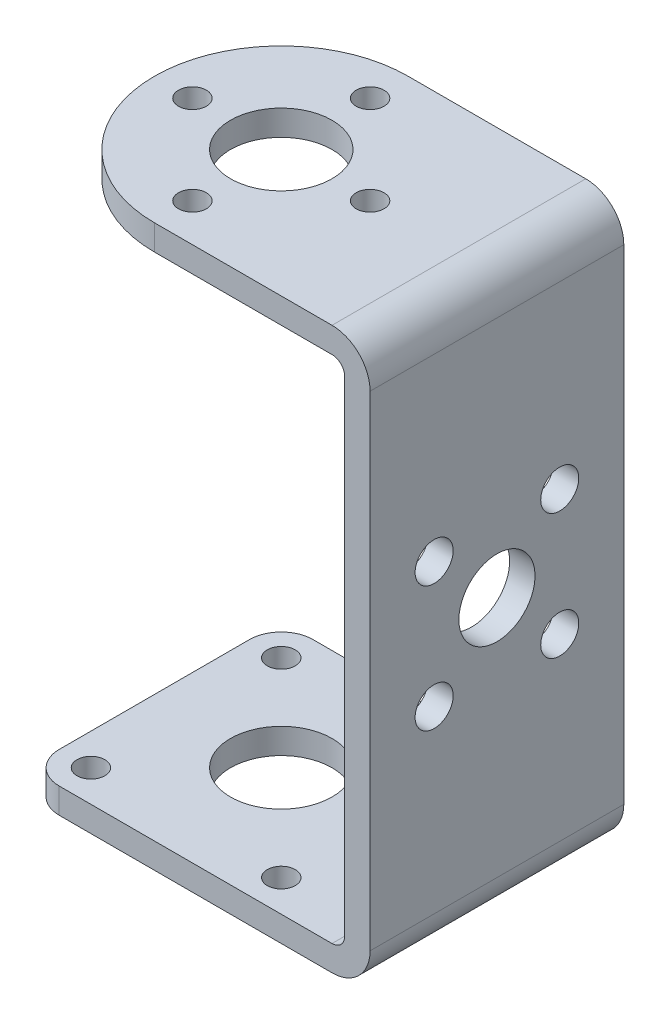
SolidWorks part; units mm, degrees
ref_plane "Front Plane" through (0, 0, 0) normal (0, 0, 1) x (1, 0, 0)
ref_plane "Top Plane" through (0, 0, 0) normal (0, 1, 0) x (1, 0, 0)
ref_plane "Right Plane" through (0, 0, 0) normal (1, 0, 0) x (0, 0, -1)
ref_plane "Plane4" through (0, -22.1, 0) normal (0, -1, 0) x (1, 0, 0)
sketch "Sketch1" plane through (0, -22.1, 0) normal (0, -1, 0) x (1, 0, 0)
  line L0 (17, 10) -> (0, 10)
  line L1 (0, -10) -> (17, -10)
  line L2 (17, -10) -> (17, 10)
  arc A0 (0, 10) -> (0, -10) centre (0, 0) ccw
extrude "Boss-Extrude1" add sketch "Sketch1" against normal blind 44.2
sketch "Sketch2" plane through (0, 0, -10) normal (0, 0, -1) x (-1, 0, 0)
  line L0 (0, -22.1) -> (0, 20.1)
  line L1 (0, 20.1) -> (-15, 20.1)
  line L2 (-15, 20.1) -> (-15, -22.1)
  line L3 (-15, -22.1) -> (0, -22.1)
extrude "Cut-Extrude1" cut sketch "Sketch2" against normal through all
sketch "Sketch3" plane through (15, 0, 0) normal (-1, 0, 0) x (0, 0, 1)
  line L0 (10, -22.1) -> (-10, -22.1)
  line L1 (-10, -22.1) -> (-10, -20.1)
  line L2 (-10, -20.1) -> (10, -20.1)
  line L3 (10, -20.1) -> (10, -22.1)
extrude "Boss-Extrude2" add sketch "Sketch3" along normal blind 25
hole_wizard "Ø3.0 (3) Diameter Hole1" positions "Sketch5" profile "Sketch4" hole size "Ø3.0" standard "ANSI Metric"
sketch "Sketch5" plane through (15, 0, 0) normal (-1, 0, 0) x (0, 0, 1)
  point P0 (4.9497, 4.9497)
  point P1 (4.9497, -4.9497)
  point P2 (-4.9497, -4.9497)
  point P3 (-4.9497, 4.9497)
sketch "Sketch4" plane through (15, 4.9497, 4.9497) normal (0, 1, 0) x (0, 0, 1)
  line L0 (0, 0) -> (0, 2)
  line L1 (0, 2) -> (1.5, 2)
  line L2 (1.5, 2) -> (1.5, 0)
  line L5 (1.5, 0) -> (0, 0)
  line L11 (0, -6.35) -> (0, 107.95) construction
  dimension "Thru Hole Dia." = 3
  dimension "Thru Hole Depth" = 2
hole_wizard "Ø6.0 (6) Diameter Hole1" positions "Sketch7" profile "Sketch6" hole size "Ø6.0" standard "ANSI Metric"
sketch "Sketch7" plane through (15, 0, 0) normal (-1, 0, 0) x (0, 0, 1)
  point P0 (0, 0)
sketch "Sketch6" plane through (15, 0, 0) normal (0, 1, 0) x (0, 0, 1)
  line L0 (0, 0) -> (0, 2)
  line L1 (0, 2) -> (3, 2)
  line L2 (3, 2) -> (3, 0)
  line L5 (3, 0) -> (0, 0)
  line L11 (0, -6.35) -> (0, 107.95) construction
  dimension "Thru Hole Dia." = 6
  dimension "Thru Hole Depth" = 2
hole_wizard "Ø8.0 (8) Diameter Hole1" positions "Sketch9" profile "Sketch8" hole size "Ø8.0" standard "ANSI Metric"
sketch "Sketch9" plane through (0, -22.1, 0) normal (0, -1, 0) x (-1, 0, 0)
  point P0 (0, 0)
sketch "Sketch8" plane through (0, -22.1, 0) normal (1, 0, 0) x (0, 0, -1)
  line L0 (0, 0) -> (0, 2)
  line L1 (0, 2) -> (4, 2)
  line L2 (4, 2) -> (4, 0)
  line L5 (4, 0) -> (0, 0)
  line L11 (0, -6.35) -> (0, 107.95) construction
  dimension "Thru Hole Dia." = 8
  dimension "Thru Hole Depth" = 2
hole_wizard "Ø2.2 (2.2) Diameter Hole2" positions "Sketch13" profile "Sketch12" hole size "Ø2.2" standard "ANSI Metric"
sketch "Sketch13" plane through (0, 20.1, 0) normal (0, -1, 0) x (-1, 0, 0)
  point P0 (0, 7)
  point P1 (7, 0)
  point P2 (0, -7)
  point P3 (-7, 0)
sketch "Sketch12" plane through (0, 20.1, -7) normal (1, 0, 0) x (0, 0, -1)
  line L0 (0, 0) -> (0, 2)
  line L1 (0, 2) -> (1.1, 2)
  line L2 (1.1, 2) -> (1.1, 0)
  line L5 (1.1, 0) -> (0, 0)
  line L11 (0, -6.35) -> (0, 107.95) construction
  dimension "Thru Hole Dia." = 2.2
  dimension "Thru Hole Depth" = 2
hole_wizard "Ø8.0 (8) Diameter Hole2" positions "Sketch15" profile "Sketch14" hole size "Ø8.0" standard "ANSI Metric"
sketch "Sketch15" plane through (0, 20.1, 0) normal (0, -1, 0) x (-1, 0, 0)
  point P0 (0, 0)
sketch "Sketch14" plane through (0, 20.1, 0) normal (1, 0, 0) x (0, 0, -1)
  line L0 (0, 0) -> (0, 2)
  line L1 (0, 2) -> (4, 2)
  line L2 (4, 2) -> (4, 0)
  line L5 (4, 0) -> (0, 0)
  line L11 (0, -6.35) -> (0, 107.95) construction
  dimension "Thru Hole Dia." = 8
  dimension "Thru Hole Depth" = 2
fillet "Fillet1" radius 1 2 edges at (15, -20.1, 0) (15, 20.1, 0)
fillet "Fillet2" radius 2.5 2 edges at (-10, -21.1, -10) (-10, -21.1, 10)
fillet "Fillet3" radius 3 2 edges at (17, 22.1, 0) (17, -22.1, 0)
sketch "Sketch16" plane through (0, 0, 10) normal (0, 0, 1) x (1, 0, 0)
  line L0 (0, -20.1) -> (0, 20.1) construction
  line L1 (-10, -20.1) -> (0, -20.1)
  line L2 (-10, -20.1) -> (-10, 20.1)
  line L3 (-10, 20.1) -> (0, 20.1)
  line L4 (0, -20.1) -> (0, 20.1)
extrude "Cut-Extrude2" cut sketch "Sketch16" against normal blind 23
sketch "Sketch17" plane through (0, -22.1, 0) normal (0, -1, 0) x (1, 0, 0)
  line L0 (0, -5.255) -> (0, 0) construction
  line L1 (0, 0) -> (-6.3929, 0) construction
  circle A0 centre (-7.5, -7.5) radius 1.1
  circle A1 centre (-7.5, 7.5) radius 1.1
  circle A2 centre (7.5, 7.5) radius 1.1
  circle A3 centre (7.5, -7.5) radius 1.1
  dimension "D1" = 2.2
  dimension "D2" = 15
  dimension "D3" = 15
extrude "Cut-Extrude3" cut sketch "Sketch17" against normal blind 23
